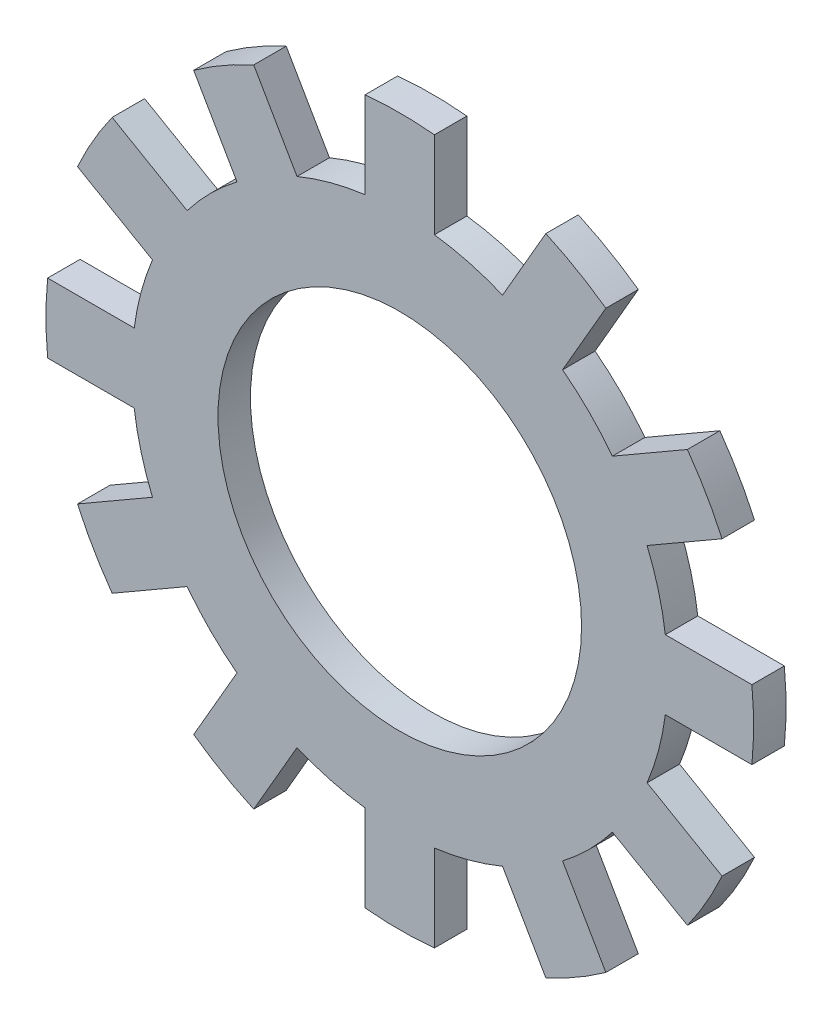
SolidWorks part; units mm, degrees
ref_plane "Front Plane" through (0, 0, 0) normal (0, 0, 1) x (1, 0, 0)
ref_plane "Top Plane" through (0, 0, 0) normal (0, 1, 0) x (1, 0, 0)
ref_plane "Right Plane" through (0, 0, 0) normal (1, 0, 0) x (0, 0, -1)
sketch "Sketch1" plane through (0, 0, 0) normal (0, 0, 1) x (1, 0, 0)
  circle A0 centre (0, 0) radius 2.725 construction
  circle A1 centre (0, 0) radius 1.4
  circle A2 centre (0, 0) radius 2.0625
  dimension "A" = 2.8
  dimension "B" = 5.45
  dimension "D1" = 4.125
extrude "Extrude1" add sketch "Sketch1" along normal blind 0.25
sketch "Sketch2" plane through (0, 0, 0) normal (0, 0, 1) x (1, 0, 0)
  line L0 (0, 0) -> (0, 2.725) construction
  line L1 (0, 0) -> (0.7053, 2.6321) construction
  line L2 (0, 0) -> (-0.7053, 2.6321) construction
  line L3 (-0.5338, 1.9922) -> (0, 1.9922) construction
  line L4 (-0.2669, 2.7119) -> (-0.2669, 2.0452)
  line L5 (0.2669, 2.7119) -> (0.2669, 2.0452)
  line L6 (-0.2669, 2.0452) -> (0.2669, 2.0452)
  circle A0 centre (0, 0) radius 2.0625 construction
  circle A1 centre (0, 0) radius 2.0625 construction
  circle A2 centre (0, 0) radius 2.725 construction
  arc A3 (0.2669, 2.7119) -> (-0.2669, 2.7119) centre (0, 0) ccw
  dimension "D2" = 15
  dimension "D3" = 15
extrude "Extrude2" add sketch "Sketch2" along normal up to surface (0.25 mm away) up to face at (2.0625, 0, 0.25)
pattern_circular "CirPattern1" count 12 over 360 about axis through (0, 0, 0) along (0, 0, 1) of "Extrude2"
sketch "Sketch3" plane through (0, 0, 0) normal (0, 0, 1) x (1, 0, 0)
  line L0 (-0.3187, 2.7063) -> (-0.3187, 2.0377)
  line L1 (0.3187, 2.7063) -> (0.3187, 2.0377)
  line L2 (0, 0) -> (0, 2.725) construction
  line L3 (0, 0) -> (0.8421, 2.5916) construction
  line L4 (0, 0) -> (-0.8421, 2.5916) construction
  line L5 (-0.6373, 1.9616) -> (0, 1.9616) construction
  line L6 (-0.3187, 2.0377) -> (0.3187, 2.0377)
  circle A0 centre (0, 0) radius 2.725 construction
  circle A1 centre (0, 0) radius 2.0625 construction
  circle A2 centre (0, 0) radius 2.0625 construction
  arc A3 (0.3187, 2.7063) -> (-0.3187, 2.7063) centre (0, 0) ccw
  dimension "D2" = 18
  dimension "D3" = 18
extrude "Extrude3" [suppressed] add sketch "Sketch3" along normal up to surface (0.25 mm away)
pattern_circular "CirPattern2" [suppressed] count 10 over 360
equation "\"D1@Sketch1\" =  ( \"B@Sketch1\" + \"A@Sketch1\" )  / 2"
